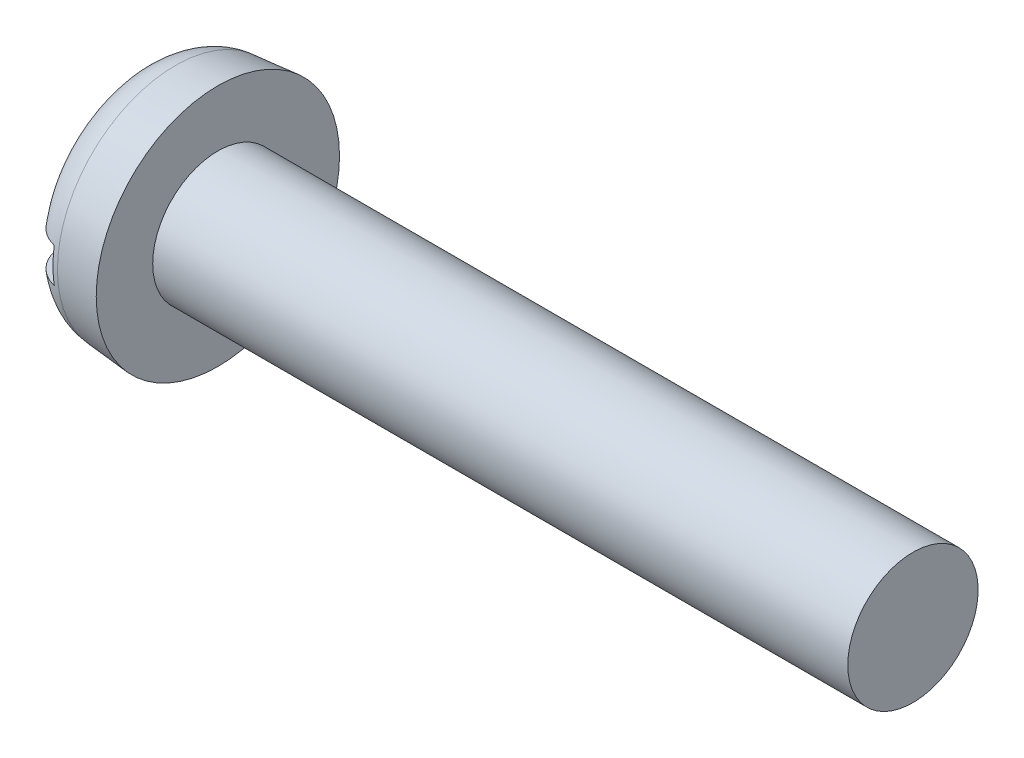
SolidWorks part; units mm, degrees
ref_plane "Plane1" through (0, 0, 0) normal (0, 0, 1) x (1, 0, 0)
ref_plane "Plane2" through (0, 0, 0) normal (0, 1, 0) x (1, 0, 0)
ref_plane "Plane3" through (0, 0, 0) normal (1, 0, 0) x (0, 0, -1)
sketch "BodySke" plane through (0, 0, 0) normal (0, 0, 1) x (1, 0, 0)
  line L0 (1.8, 1.5) -> (1.8, 2.8)
  line L1 (0, 0) -> (0, 2.6425)
  line L2 (-25.4, 0) -> (127, 0) construction
  line L3 (17.8, 0) -> (0, 0)
  line L4 (1.8, 1.5) -> (17.8, 1.5)
  line L5 (17.8, 1.5) -> (17.8, 0)
  line L6 (0, 2.6425) -> (1.8, 2.8)
  line L9 (2.3, 3.0875) -> (2.3, -6.4375) construction
  line L10 (1.8, 6.35) -> (1.8, -3.175) construction
  dimension "Head_ht" = 1.8
  dimension "Diameter" = 3
  dimension "Length" = 16
  dimension "Head_dia" = 5.6
  dimension "Advance" = 0.5
  dimension "Thread_nom" = 16
  dimension "Head_side_angle" = 5
revolve "Base-Revolve" add sketch "BodySke"
cosmetic thread "ThreadCosmetic" [suppressed]
fillet "Fillet1" [suppressed] radius 0.1
fillet "Fillet2" radius 0.9 1 edges at (0, 0, 2.6425)
sketch "Sketch2" plane through (0, 0, 0) normal (1, 0, 0) x (0, 0, -1)
  line L0 (2.8, -0.4) -> (-2.8, -0.4)
  line L1 (2.8, -0.4) -> (2.8, 0.4)
  line L2 (-2.8, 0.4) -> (2.8, 0.4)
  line L3 (-2.8, 0.4) -> (-2.8, -0.4)
  dimension "D1" = 5.6
  dimension "D2" = 2.8
  dimension "Slot_width" = 0.8
  dimension "D3" = 0.4
extrude "Slot" cut sketch "Sketch2" along normal blind 0.7
sketch "ThdSchSke" plane through (0, 0, 0) normal (0, 0, 1) x (1, 0, 0)
  line L0 (2.8, -1.2195) -> (2.6036, -1.5)
  line L1 (2.8, -1.2195) -> (2.9964, -1.5)
  line L2 (2.9964, -1.5) -> (2.9964, -1.875)
  line L3 (-3.175, 0) -> (5.1513, 0) construction
  line L5 (2.9964, -1.875) -> (2.6036, -1.875)
  line L6 (2.6036, -1.875) -> (2.6036, -1.5)
  dimension "Thread_minor" = 2.439
  dimension "Diameter" = 3
  dimension "Start" = 2.8
  dimension "SideAngle" = 55
  dimension "VeeAngle" = 70
  dimension "Overcut" = 3.75
revolve "ThreadSchematic" [suppressed] cut sketch "ThdSchSke" angle 360 about L3
pattern_linear "ThdSchPat" [suppressed]
equation "\"D1@Sketch2\" = \"Head_dia@BodySke\""
equation "\"D2@Sketch2\" = \"D1@Sketch2\" / 2"
equation "\"D3@Sketch2\" = \"Slot_width@Sketch2\" / 2"
equation "\"Thread_length@ThreadCosmetic\" = ((sgn( (\"Length@BodySke\" - \"Advance@BodySke\" * 2.0 ) - \"Thread_nom@BodySke\" )-1)*( (\"Length@BodySke\" - \"Advance@BodySke\"  * 2.0) - \"Thread_nom@BodySke\" ))/-2+ \"Thread_nom@BodySke\""
equation "\"Thread_minor@ThdSchSke\" = \"Thread_minor@ThreadCosmetic\""
equation "\"Diameter@ThdSchSke\" = \"Diameter@BodySke\""
equation "\"Overcut@ThdSchSke\" = \"Diameter@BodySke\" * 1.25"
equation "\"Start@ThdSchSke\" = \"Head_ht@BodySke\" + \"Length@BodySke\" - \"Thread_length@ThreadCosmetic\"  '---Non-countersunk---"
equation "\"Num_threads@ThdSchPat\" = int( \"Thread_length@ThreadCosmetic\" / \"Advance@BodySke\" + 0.999 )  + 1"
equation "\"Advance@ThdSchPat\" = \"Thread_length@ThreadCosmetic\" /  (\"Num_threads@ThdSchPat\" - 1) 'relax it"
